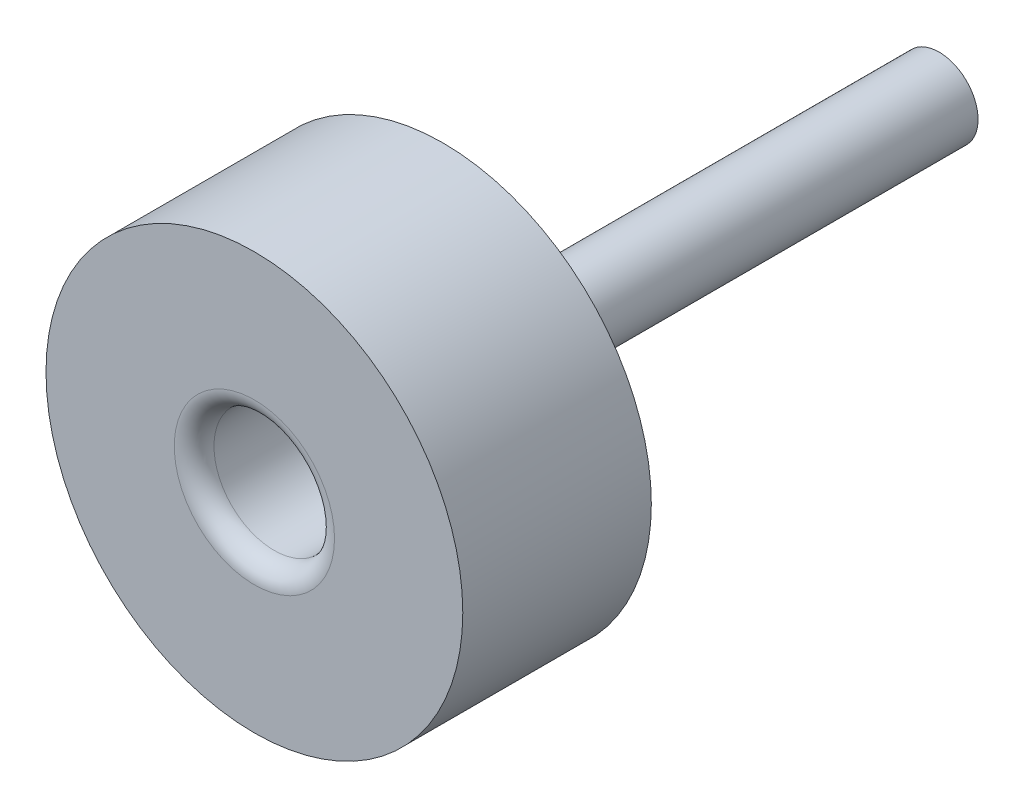
SolidWorks part; units mm, degrees
ref_plane "Ebene vorne" through (0, 0, 0) normal (0, 0, 1) x (1, 0, 0)
ref_plane "Ebene oben" through (0, 0, 0) normal (0, 1, 0) x (1, 0, 0)
ref_plane "Ebene rechts" through (0, 0, 0) normal (1, 0, 0) x (0, 0, -1)
sketch "Skizze1" plane through (0, 0, 0) normal (0, 0, 1) x (1, 0, 0)
  circle A0 centre (0, 0) radius 6
  dimension "D1" = 12
extrude "Aufsatz-Linear austragen1" add sketch "Skizze1" along normal blind 9
sketch "Skizze2" plane through (0, 0, 0) normal (0, 0, -1) x (-1, 0, 0)
  circle A0 centre (0, 0) radius 3.925
  dimension "D1" = 7.85
extrude "Aufsatz-Linear austragen2" add sketch "Skizze2" along normal blind 41
sketch "Skizze3" plane through (0, 0, 9) normal (0, 0, 1) x (1, 0, 0)
  circle A0 centre (0, 0) radius 21
  dimension "D1" = 42
extrude "Aufsatz-Linear austragen3" add sketch "Skizze3" along normal blind 19
sketch "Skizze4" plane through (0, 0, 28) normal (0, 0, 1) x (1, 0, 0)
  circle A0 centre (0, 0) radius 6.075
  dimension "D1" = 12.15
extrude "Schnitt-Linear austragen2" cut sketch "Skizze4" against normal blind 10
fillet "Verrundung1" radius 2 1 edges at (6.075, 0, 28)
sketch "Skizze5" plane through (0, 0, -41) normal (0, 0, -1) x (-1, 0, 0)
  circle A0 centre (0, 0) radius 1.5
  dimension "D1" = 3
extrude "Schnitt-Linear austragen3" cut sketch "Skizze5" against normal blind 15
